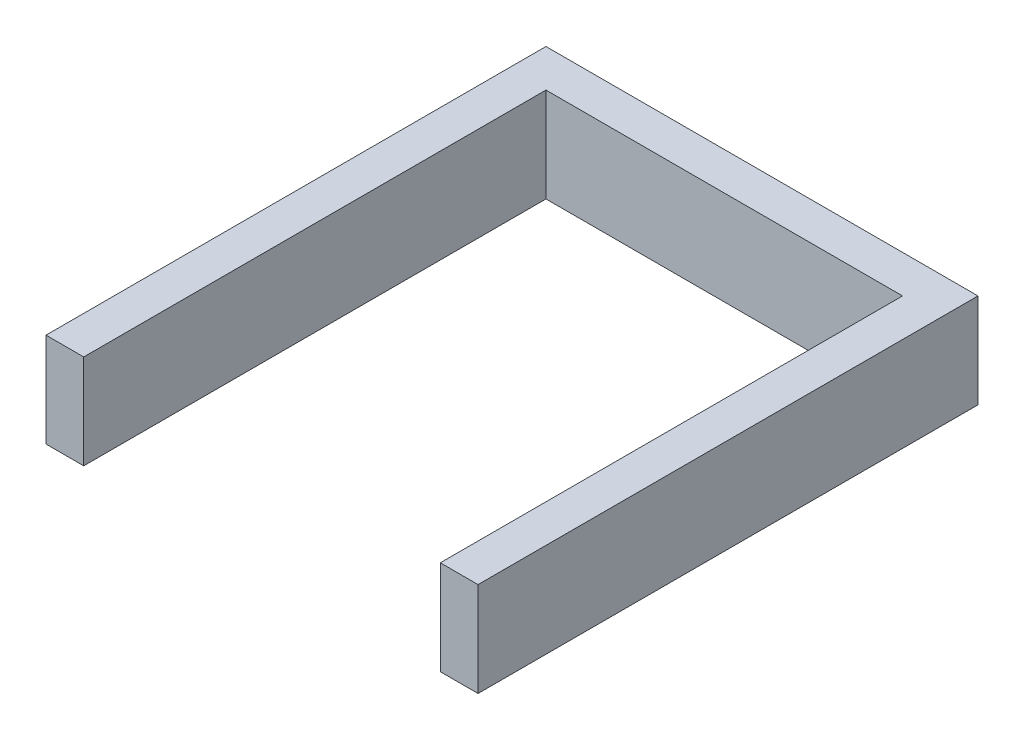
SolidWorks part; units mm, degrees
ref_plane "Front Plane" through (0, 0, 0) normal (0, 0, 1) x (1, 0, 0)
ref_plane "Top Plane" through (0, 0, 0) normal (0, 1, 0) x (1, 0, 0)
ref_plane "Right Plane" through (0, 0, 0) normal (1, 0, 0) x (0, 0, -1)
sketch "Sketch2" plane through (0, 0, 0) normal (0, 1, 0) x (1, 0, 0)
  line L0 (-2, 0) -> (-2, 26.5)
  line L2 (0, 0) -> (0, 24.5)
  line L3 (0, 24.5) -> (18.9, 24.5)
  line L4 (18.9, 0) -> (18.9, 24.5)
  line L5 (-2, 26.5) -> (20.9, 26.5)
  line L6 (20.9, 0) -> (20.9, 26.5)
  line L7 (-2, 0) -> (0, 0)
  line L8 (18.9, 0) -> (20.9, 0)
  dimension "D2" = 18.9
  dimension "D3" = 24.5
  dimension "D1" = 2
extrude "Boss-Extrude1" add sketch "Sketch2" along normal blind 5
